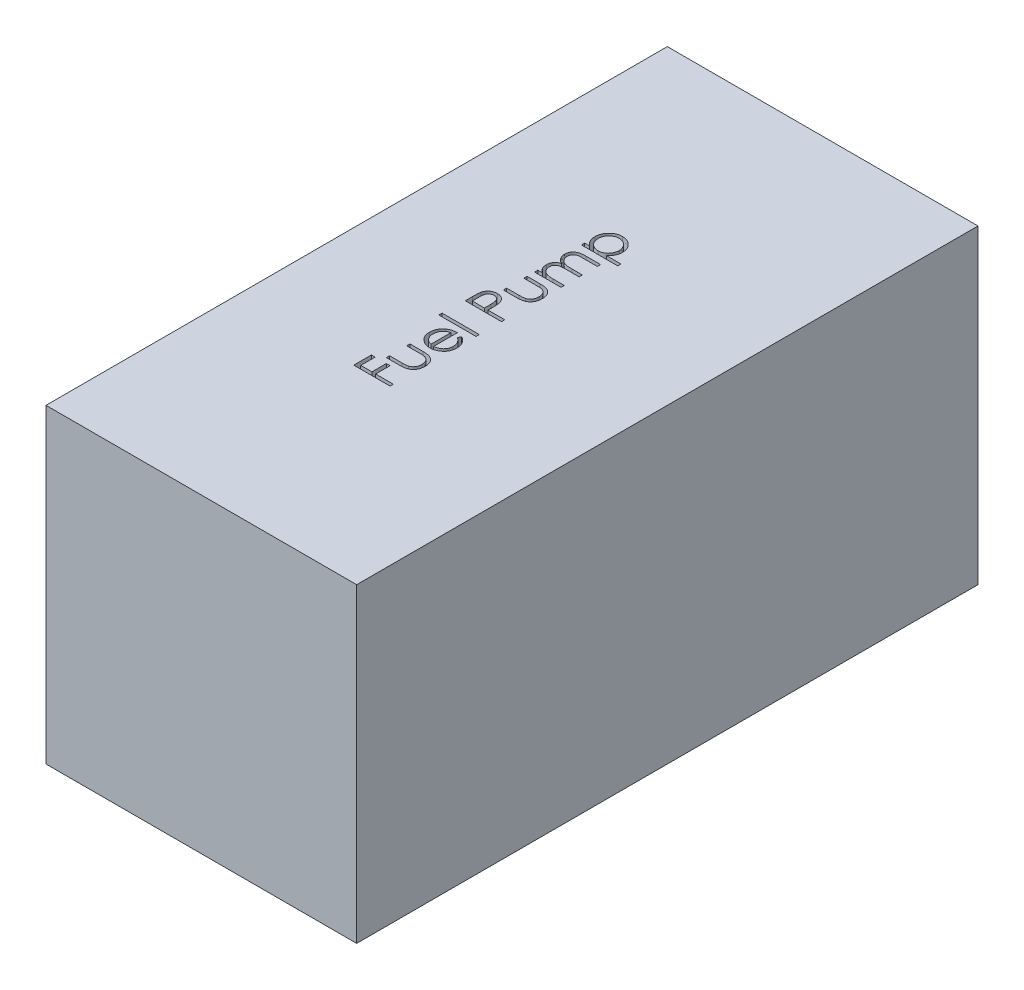
SolidWorks part; units mm, degrees
ref_plane "Front Plane" through (0, 0, 0) normal (0, 0, 1) x (1, 0, 0)
ref_plane "Top Plane" through (0, 0, 0) normal (0, 1, 0) x (1, 0, 0)
ref_plane "Right Plane" through (0, 0, 0) normal (1, 0, 0) x (0, 0, -1)
sketch "Sketch1" plane through (0, 0, 0) normal (0, 1, 0) x (1, 0, 0)
  line L1 (-15, 30) -> (15, 30)
  line L2 (-15, 30) -> (-15, -30)
  line L3 (-15, -30) -> (15, -30)
  line L4 (15, 30) -> (15, -30)
  line L5 (-15, 30) -> (15, -30) construction
  line L6 (-15, -30) -> (15, 30) construction
  point P0 (0, 0)
  dimension "D1" = 30
  dimension "D2" = 60
extrude "Boss-Extrude1" add sketch "Sketch1" along normal blind 30
sketch "Sketch2" plane through (0, 30, 0) normal (0, 1, 0) x (1, 0, 0)
  line L0 (0, -30) -> (0, 30) construction
  line L1 (-15, -30) -> (15, -30) construction
  line L2 (15, 30) -> (-15, 30) construction
  text T0 "Fuel Pump"
extrude "Cut-Extrude1" cut sketch "Sketch2" against normal blind 2
